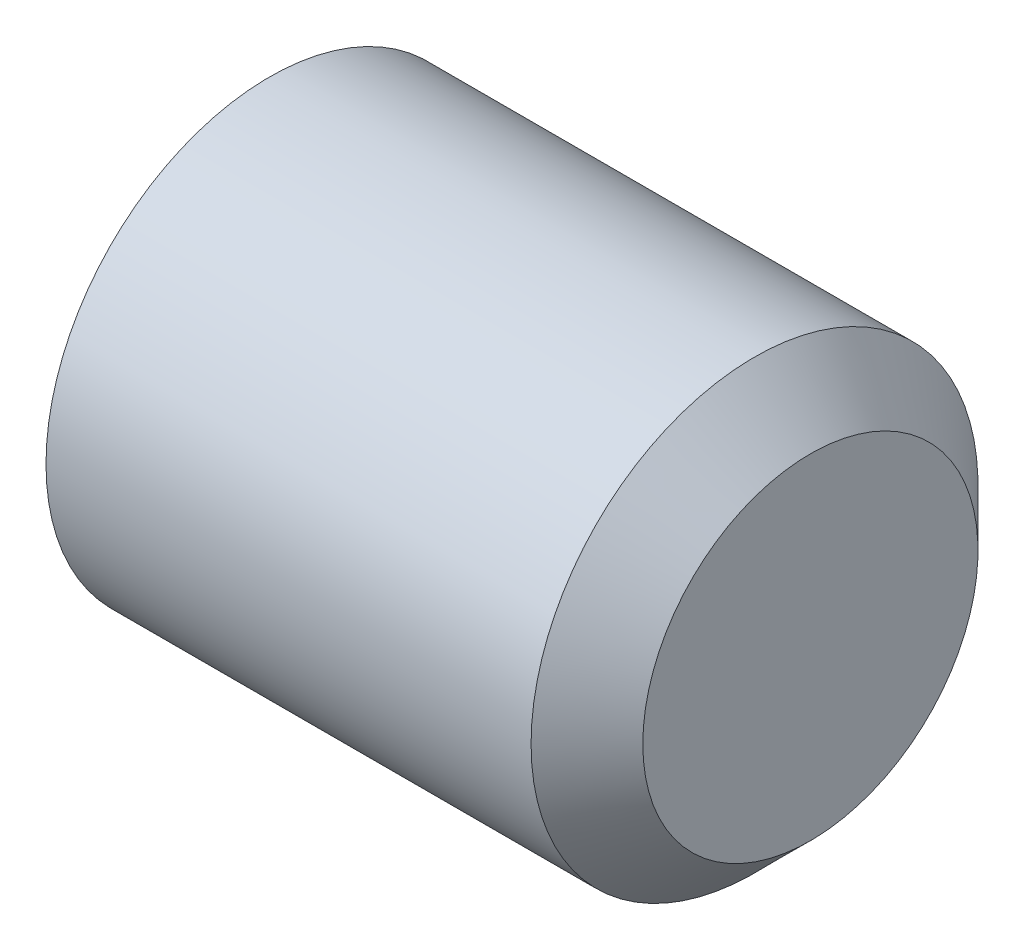
SolidWorks part; units mm, degrees
revolve "BaseBody" add sketch "BodySke" angle 360 about L5
sketch "BodySke" plane through (0, 0, 0) normal (0, 0, 1) x (1, 0, 0)
  line L0 (0, 0) -> (0, 10.352)
  line L1 (0, 10.352) -> (0.9515, 12)
  line L2 (0.9515, 12) -> (27, 12)
  line L3 (27, 12) -> (30, 9)
  line L4 (30, 0) -> (0, 0)
  line L5 (-12.7, 0) -> (88.9, 0) construction
  line L6 (30, 9) -> (30, 0)
  line L7 (30, 9) -> (30, 18.525) construction
  line L8 (0, -10.352) -> (0.9515, -12) construction
  line L9 (3, 15.875) -> (3, -3.175) construction
  line L10 (27, -12) -> (30, -9) construction
  dimension "Diameter" = 24
  dimension "Drive_ch_ang" = 60
  dimension "Minor_dia" = 20.704
  dimension "Cup_nose_ang" = 45
  dimension "Cup_dia" = 18
  dimension "Length" = 30
  dimension "Advance" = 3
cosmetic thread "ThreadCosmetic" [suppressed] parameters "Thread_minor"=20.704
ref_plane "Plane1" through (0, 0, 0) normal (0, 0, 1) x (1, 0, 0)
ref_plane "Plane2" through (0, 0, 0) normal (0, 1, 0) x (1, 0, 0)
ref_plane "Plane3" through (0, 0, 0) normal (1, 0, 0) x (0, 0, -1)
sketch "Sketch2" plane through (0, 0, 0) normal (-1, 0, 0) x (0, 0, 1)
  line L0 (3.4641, 6) -> (-3.4641, 6)
  line L1 (-3.4641, 6) -> (-6.9282, 0)
  line L2 (3.4641, 6) -> (6.9282, 0)
  line L3 (3.4641, -6) -> (6.9282, 0)
  line L4 (3.4641, -6) -> (-3.4641, -6)
  line L5 (-3.4641, -6) -> (-6.9282, 0)
  dimension "Hex_size" = 12
  dimension "D2" = 6
  dimension "D3" = 6
extrude "Hex" [suppressed] cut sketch "Sketch2" against normal blind 12
sketch "Sketch4" plane through (0, 4.7709, -0.5249) normal (-1, 0, 0) x (0, 0, 1)
  line L0 (0.5249, -4.7709) -> (8.1959, -4.7709)
  line L1 (0.5249, -4.7709) -> (6.6732, -1.2211) construction
  line L2 (0.5249, -4.7709) -> (4.3604, 1.8724)
  line L3 (6.7899, -3.1774) -> (7.8687, -2.5545)
  line L4 (5.0374, -0.142) -> (6.1162, 0.4809)
  arc A0 (6.7899, -3.1774) -> (5.0374, -0.142) centre (0.5249, -4.7709) ccw
  arc A1 (8.1959, -4.7709) -> (7.8687, -2.5545) centre (0.5249, -4.7709) ccw
  arc A2 (4.3604, 1.8724) -> (6.1162, 0.4809) centre (0.5249, -4.7709) cw
  circle A3 centre (0.5249, -4.7709) radius 6.4645 construction
  circle A4 centre (0.5249, -4.7709) radius 7.671 construction
  dimension "Spline_n_dim" = 12.929
  dimension "Spline_m_dim" = 15.342
  dimension "D1" = 30
  dimension "Spline_a_dim" = 60
  dimension "Spline_p_dim" = 3.505
  dimension "D3" = 1.7525
extrude "Spline6" [suppressed] cut sketch "Sketch4" against normal blind 12
pattern_circular "CirPattern1" [suppressed] count 6 every 60 about axis through (-12.7, 0, 0) along (1, 0, 0)
sketch "Sketch5" plane through (0, 0.6556, 6.6316) normal (-1, 0, 0) x (0, 0, 1)
  line L0 (-6.6316, -0.6556) -> (1.0394, -0.6556)
  line L1 (-6.6316, -0.6556) -> (-1.6115, 4.3645) construction
  line L2 (-6.6316, -0.6556) -> (-6.6316, 7.0154)
  line L3 (-0.8213, 2.6763) -> (-0.1116, 3.386)
  line L4 (-3.2997, 5.1547) -> (-2.5901, 5.8644)
  line L5 (-3.2997, 5.1547) -> (-0.8213, 2.6763)
  arc A1 (1.0394, -0.6556) -> (-0.1116, 3.386) centre (-6.6316, -0.6556) ccw
  arc A2 (-6.6316, 7.0154) -> (-2.5901, 5.8644) centre (-6.6316, -0.6556) cw
  circle A3 centre (-6.6316, -0.6556) radius 6.4645 construction
  circle A4 centre (-6.6316, -0.6556) radius 7.671 construction
  dimension "Spline_n_dim" = 12.929
  dimension "Spline_m_dim" = 15.342
  dimension "Spline_p_dim" = 3.505
  dimension "D3" = 1.7525
  dimension "D1" = 45
  dimension "Spline_a_dim" = 90
extrude "Spline4" [suppressed] cut sketch "Sketch5" against normal blind 12
pattern_circular "CirPattern2" [suppressed] count 4 every 90 about axis through (-12.7, 0, 0) along (1, 0, 0)
sketch "ThdSchSke" plane through (0, 0, 0) normal (0, 0, 1) x (1, 0, 0)
  line L0 (0.9515, -10.352) -> (-0.2025, -12)
  line L1 (0.9515, -10.352) -> (2.1054, -12)
  line L2 (2.1054, -12) -> (2.1054, -15)
  line L3 (-3.175, 0) -> (5.1513, 0) construction
  line L4 (0.9515, 12) -> (0.9515, -12) construction
  line L5 (2.1054, -15) -> (-0.2025, -15)
  line L6 (-0.2025, -15) -> (-0.2025, -12)
  dimension "Thread_minor" = 20.704
  dimension "Diameter" = 24
revolve "ThreadSchematic" [suppressed] cut sketch "ThdSchSke" angle 360 about L3
pattern_linear "ThdSchPat" [suppressed]
equation "\"D2@Sketch2\" = \"Hex_size@Sketch2\" / 2"
equation "\"D3@Sketch2\" = \"Hex_size@Sketch2\" / 2"
equation "\"Thread_minor@ThreadCosmetic\" = \"Minor_dia@BodySke\""
equation "\"D1@Sketch4\" = \"Spline_a_dim@Sketch4\" / 2"
equation "\"D3@Sketch4\" = \"Spline_p_dim@Sketch4\" / 2"
equation "\"D2@CirPattern1\" = \"Spline_a_dim@Sketch4\""
equation "\"Num_teeth@CirPattern1\" = 360 / \"D2@CirPattern1\""
equation "\"Spline_a_dim@Sketch5\" = 90"
equation "\"Spline_p_dim@Sketch5\" = \"Spline_p_dim@Sketch4\""
equation "\"Spline_m_dim@Sketch5\" = \"Spline_m_dim@Sketch4\""
equation "\"Spline_n_dim@Sketch5\" = \"Spline_n_dim@Sketch4\""
equation "\"D1@Sketch5\" = \"Spline_a_dim@Sketch5\" / 2"
equation "\"D3@Sketch5\" = \"Spline_p_dim@Sketch5\" / 2"
equation "\"Key_eng@Spline4\" = \"Key_eng@Spline6\""
equation "\"Thread_minor@ThdSchSke\" = \"Thread_minor@ThreadCosmetic\""
equation "\"Diameter@ThdSchSke\" = \"Diameter@BodySke\""
equation "\"Overcut@ThdSchSke\" = \"Diameter@BodySke\" * 1.25"
equation "\"Num_threads@ThdSchPat\" = int( (\"Length@BodySke\" - ( ( ( \"Diameter@BodySke\" - \"Minor_dia@BodySke\" ) * 0.5 ) / tan( \"Drive_ch_ang@BodySke\" * 0.017453292 ) ) - ( ( ( \"Diameter@BodySke\" - \"Cup_dia@BodySke\" ) * 0.5 ) * tan( \"Cup_nose_ang@BodySke\" * 0.017453292 ) ) ) / \"Advance@BodySke\" + 0.999 )  + 1"
equation "\"Advance@ThdSchPat\" = (\"Length@BodySke\" - ( ( ( \"Diameter@BodySke\" - \"Minor_dia@BodySke\" ) * 0.5 ) / tan( \"Drive_ch_ang@BodySke\" * 0.017453292 ) ) - ( ( ( \"Diameter@BodySke\" - \"Cup_dia@BodySke\" ) * 0.5 ) * tan( \"Cup_nose_ang@BodySke\" * 0.017453292 ) ) ) /  (\"Num_threads@ThdSchPat\" - 1) 'relax it"
equation "' \"Num_threads@ThdSchPat\" = \"Num_threads@ThdSchPat\" - sgn( \"Num_threads@ThdSchPat\" - 1) '---chamfered tips only---"
